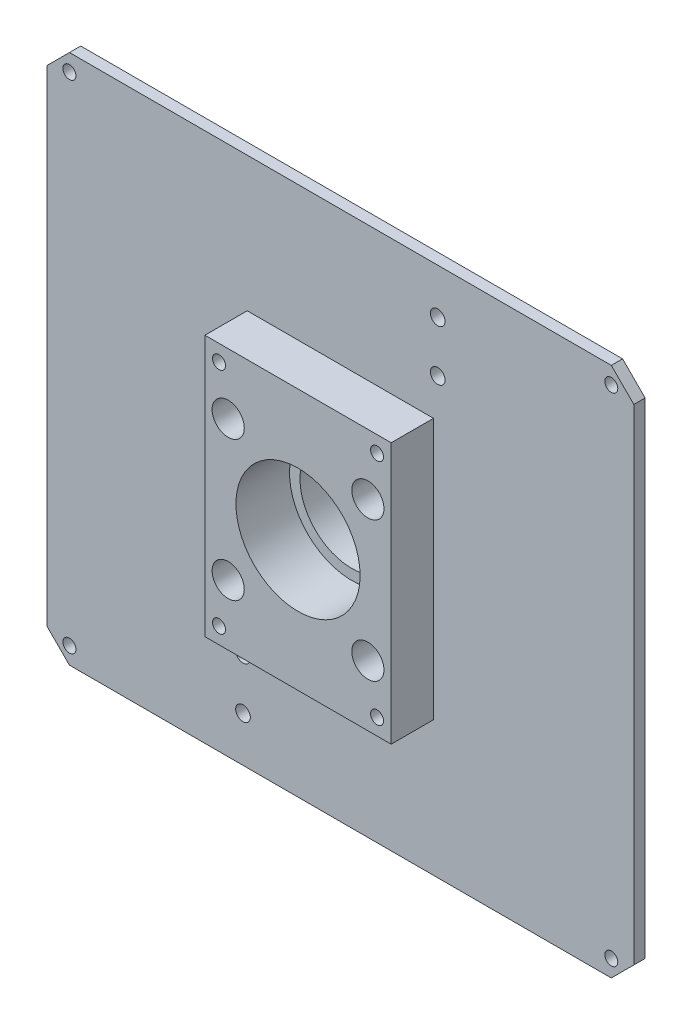
SolidWorks part; units mm, degrees
ref_plane "Front Plane" through (0, 0, 0) normal (0, 0, 1) x (1, 0, 0)
ref_plane "Top Plane" through (0, 0, 0) normal (0, 1, 0) x (1, 0, 0)
ref_plane "Right Plane" through (0, 0, 0) normal (1, 0, 0) x (0, 0, -1)
sketch "Sketch1" plane through (0, 0, 0) normal (0, 0, 1) x (1, 0, 0)
  line L0 (-37, -43) -> (37, -43)
  line L1 (37, -43) -> (43, -37)
  line L2 (43, -37) -> (43, 37)
  line L3 (43, 37) -> (37, 43)
  line L4 (37, 43) -> (-37, 43)
  line L5 (-37, 43) -> (-43, 37)
  line L6 (-43, 37) -> (-43, -37)
  line L7 (-43, -37) -> (-37, -43)
  circle A0 centre (0, 0) radius 18.3
  circle A1 centre (-24.7487, -24.7487) radius 4.65
  circle A2 centre (-24.7487, 24.7487) radius 4.65
  circle A3 centre (24.7487, -24.7487) radius 4.65
  circle A4 centre (24.7487, 24.7487) radius 4.65
extrude "Integral HOLT flange and stem cavity" add sketch "Sketch1" along normal blind 23
sketch "Sketch2" plane through (0, 0, 0) normal (0, 0, 1) x (1, 0, 0)
  line L0 (-96, -94) -> (96, -94)
  line L1 (96, -94) -> (104, -86)
  line L2 (104, -86) -> (104, 86)
  line L3 (104, 86) -> (96, 94)
  line L4 (96, 94) -> (-96, 94)
  line L5 (-96, 94) -> (-104, 86)
  line L6 (-104, 86) -> (-104, -86)
  line L7 (-104, -86) -> (-96, -94)
  circle A0 centre (0, 0) radius 22
  circle A1 centre (-24.7487, -24.7487) radius 5.7
  circle A2 centre (-24.7487, 24.7487) radius 5.7
  circle A3 centre (24.7487, -24.7487) radius 5.7
  circle A4 centre (24.7487, 24.7487) radius 5.7
  circle A5 centre (-96, -88) radius 2.3
  circle A6 centre (-96, 88) radius 2.3
  circle A7 centre (96, -88) radius 2.3
  circle A8 centre (96, 88) radius 2.3
  circle A9 centre (34.5, 60) radius 2.6
  circle A10 centre (34.5, 78) radius 2.6
  circle A11 centre (-34.5, -60) radius 2.6
  circle A12 centre (-34.5, -78) radius 2.6
extrude "Shared flat load plate for both cylinder mounts" add sketch "Sketch2" along normal blind 4 from offset 23
sketch "Sketch3" plane through (0, 0, 0) normal (0, 0, 1) x (1, 0, 0)
  line L0 (-33, -46.25) -> (33, -46.25)
  line L1 (33, -46.25) -> (33, 46.25)
  line L2 (33, 46.25) -> (-33, 46.25)
  line L3 (-33, 46.25) -> (-33, -46.25)
  circle A0 centre (0, 0) radius 22
  circle A1 centre (-24.7487, -24.7487) radius 5.7
  circle A2 centre (-24.7487, 24.7487) radius 5.7
  circle A3 centre (24.7487, -24.7487) radius 5.7
  circle A4 centre (24.7487, 24.7487) radius 5.7
  circle A5 centre (-28, -40.5) radius 2.3
  circle A6 centre (-28, 40.5) radius 2.3
  circle A7 centre (28, -40.5) radius 2.3
  circle A8 centre (28, 40.5) radius 2.3
extrude "Lower bearing and guide register" add sketch "Sketch3" along normal blind 15 from offset 27
